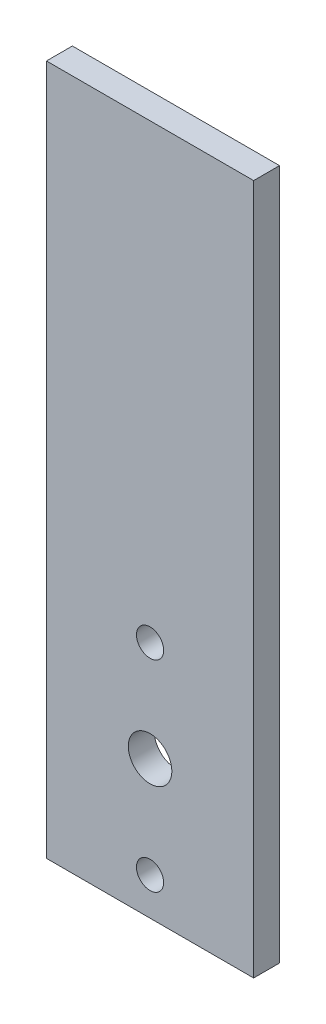
SolidWorks part; units mm, degrees
ref_plane "Front Plane" through (0, 0, 0) normal (0, 0, 1) x (1, 0, 0)
ref_plane "Top Plane" through (0, 0, 0) normal (0, 1, 0) x (1, 0, 0)
ref_plane "Right Plane" through (0, 0, 0) normal (1, 0, 0) x (0, 0, -1)
sketch "Sketch1" plane through (0, 0, 0) normal (0, 0, 1) x (1, 0, 0)
  line L0 (19.05, 43.9) -> (19.05, 6.9) construction
  line L1 (0, 0) -> (38.1, 0)
  line L2 (0, 0) -> (0, 127)
  line L3 (0, 127) -> (38.1, 127)
  line L4 (38.1, 0) -> (38.1, 127)
  circle A1 centre (19.05, 25.4) radius 4
  circle A2 centre (19.05, 6.9) radius 2.5
  circle A3 centre (19.05, 43.9) radius 2.5
  point P5 (19.05, 0)
  point P12 (19.05, 25.4)
  dimension "D3" = 5
  dimension "D4" = 8
  dimension "D5" = 5
  dimension "D1" = 38.1
  dimension "D2" = 127
  dimension "D6" = 25.4
  dimension "D7" = 37
extrude "Boss-Extrude1" add sketch "Sketch1" along normal blind 4.7625
